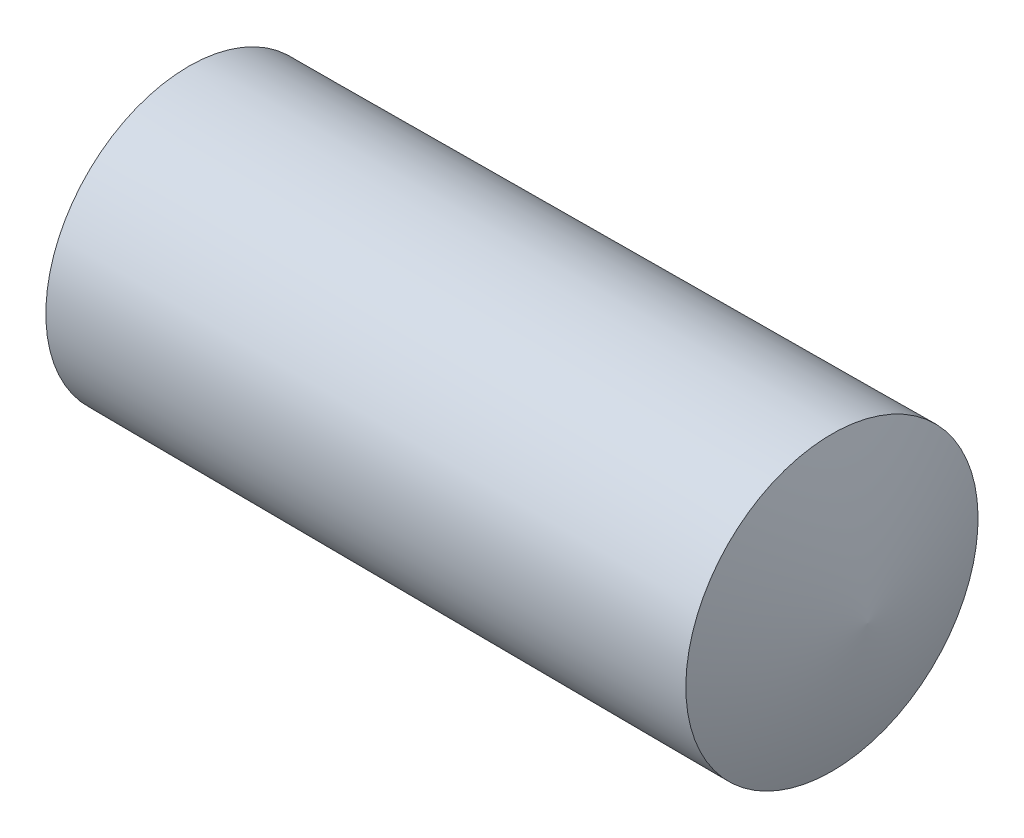
SolidWorks part; units mm, degrees
material "不锈钢"
ref_plane "前视" through (0, 0, 0) normal (0, 0, 1) x (1, 0, 0)
ref_plane "上视" through (0, 0, 0) normal (0, 1, 0) x (1, 0, 0)
ref_plane "右视" through (0, 0, 0) normal (1, 0, 0) x (0, 0, -1)
sketch "草图1" plane through (0, 0, 0) normal (0, 0, 1) x (1, 0, 0)
  line L0 (-2.32, 2) -> (6.68, 2.0444) construction
  line L1 (-2.82, 0) -> (7.18, 0)
  line L2 (0, 0) -> (1.2454, 0) construction
  line L6 (-2.32, -2) -> (6.68, -2.0444)
  arc A0 (7.18, 0) -> (6.68, -2.0444) centre (-1.0281, 0.9241) cw
  arc A1 (-2.82, 0) -> (-2.32, -2) centre (5.1264, 0.9241) ccw
  dimension "r2" = 8.26
  dimension "r1" = 8
  dimension "D1" = 10
  dimension "a" = 0.5
  dimension "D3" = 0.5
  dimension "D/2" = 4
revolve "基体-旋转" add sketch "草图1" angle 360 about L2
equation "\"r1@草图1\" = \"D/2@草图1\" * 2"
equation "\"D3@草图1\" = \"a@草图1\""
equation "\"r2@草图1\" = \"a@草图1\" / 2 + \"D/2@草图1\" * 2 + (  0.02 * \"D1@草图1\" ) * (  0.02 * \"D1@草图1\" ) / (  8 * \"a@草图1\"  ) "
